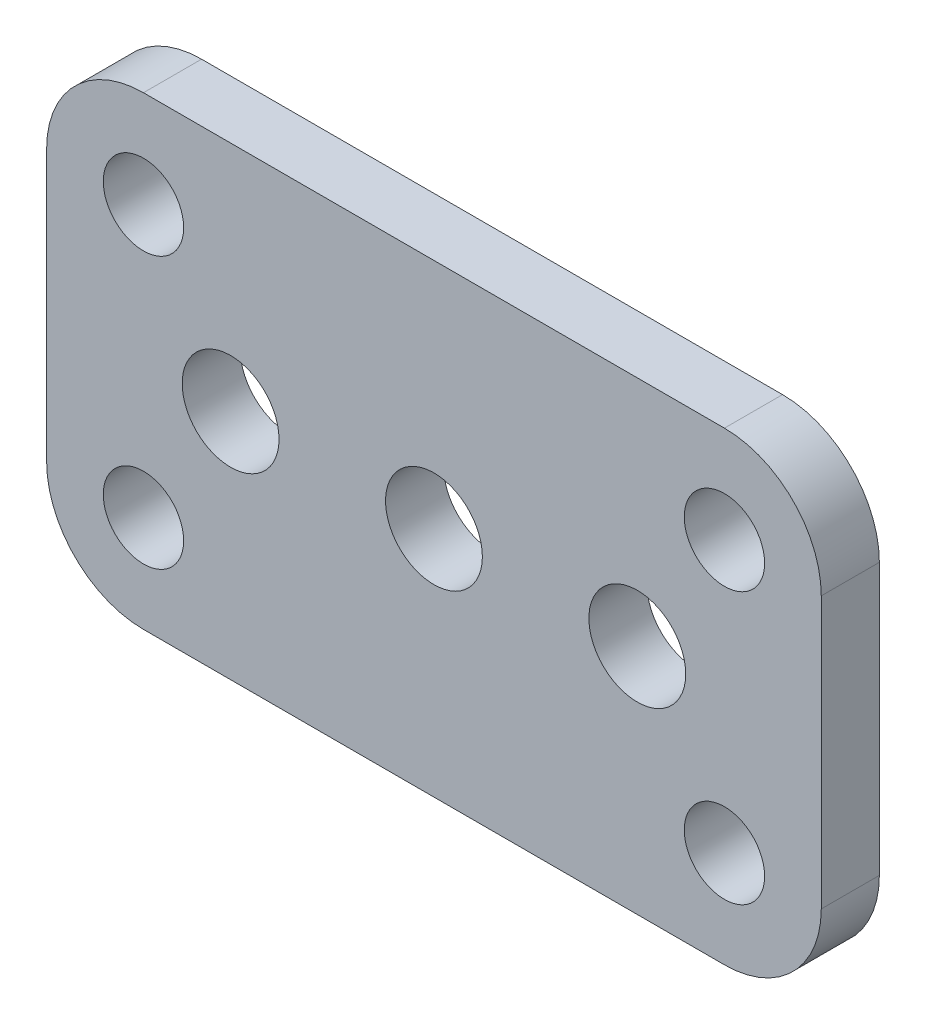
SolidWorks part; units mm, degrees
ref_plane "Plan de face" through (0, 0, 0) normal (0, 0, 1) x (1, 0, 0)
ref_plane "Plan de dessus" through (0, 0, 0) normal (0, 1, 0) x (1, 0, 0)
ref_plane "Plan de droite" through (0, 0, 0) normal (1, 0, 0) x (0, 0, -1)
sketch "Esquisse1" plane through (0, 0, 0) normal (0, 0, 1) x (1, 0, 0)
  line L1 (20, -7) -> (20, 7)
  line L2 (-15, -12) -> (15, -12)
  line L3 (-20, 7) -> (-20, -7)
  line L5 (15, 12) -> (-15, 12)
  arc A0 (20, 7) -> (15, 12) centre (15, 7) ccw
  arc A1 (15, -12) -> (20, -7) centre (15, -7) ccw
  arc A2 (-20, -7) -> (-15, -12) centre (-15, -7) ccw
  arc A3 (-15, 12) -> (-20, 7) centre (-15, 7) ccw
  circle A4 centre (0, 0) radius 2.5
  circle A5 centre (-10.5, 0) radius 2.5
  circle A6 centre (10.5, 0) radius 2.5
  circle A7 centre (-15, 7) radius 2.075
  circle A8 centre (15, 7) radius 2.075
  circle A9 centre (15, -7) radius 2.075
  circle A10 centre (-15, -7) radius 2.075
  dimension "D1" = 5
  dimension "D12" = 5
  dimension "D13" = 4.15
  dimension "D2" = 10.5
  dimension "D3" = 10.5
  dimension "D4" = 15
  dimension "D5" = 15
  dimension "D6" = 14
  dimension "D7" = 7
  dimension "D8" = 24
  dimension "D9" = 40
  dimension "D10" = 20
  dimension "D11" = 12
extrude "Boss.-Extru.1" add sketch "Esquisse1" along normal blind 3
